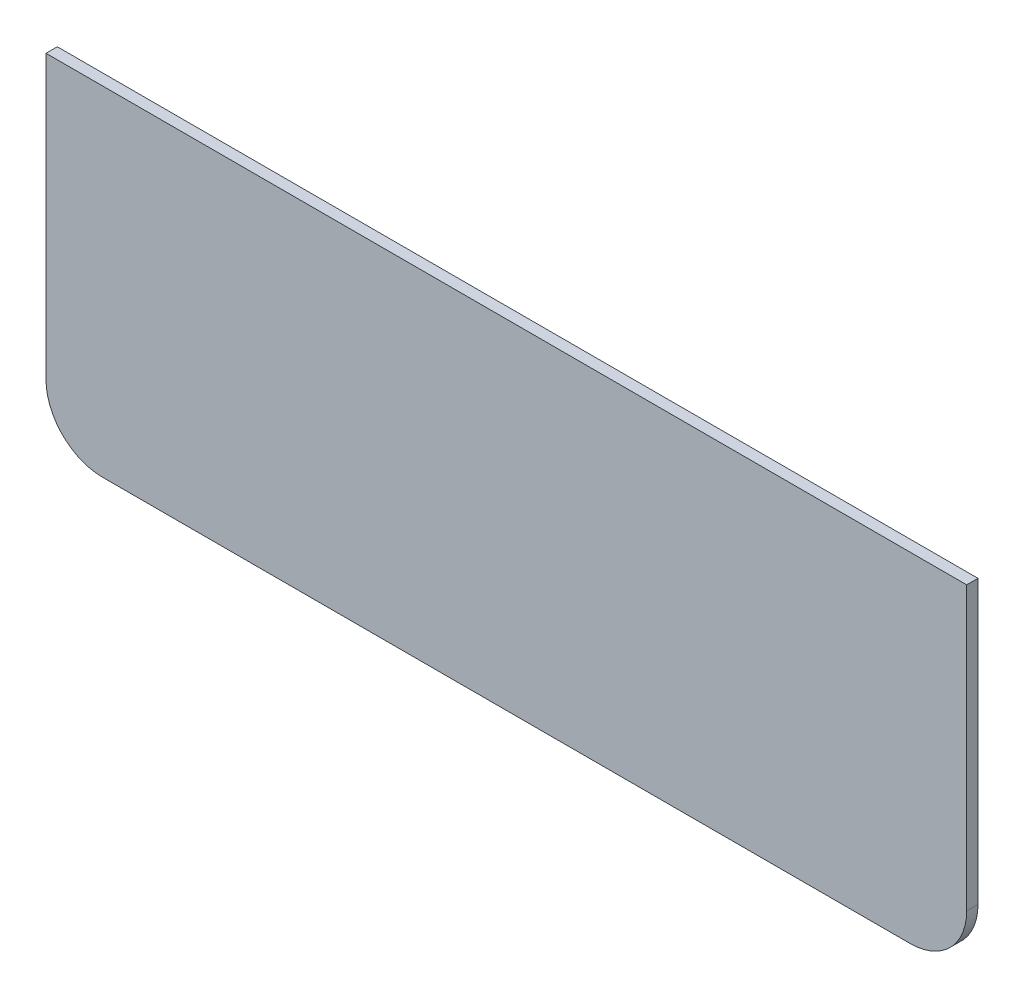
SolidWorks part; units mm, degrees
material "AISI 304"
ref_plane "Спереди" through (0, 0, 0) normal (0, 0, 1) x (1, 0, 0)
ref_plane "Сверху" through (0, 0, 0) normal (0, 1, 0) x (1, 0, 0)
ref_plane "Справа" through (0, 0, 0) normal (1, 0, 0) x (0, 0, -1)
sketch "Эскиз1" plane through (0, 0, 0) normal (0, 0, 1) x (1, 0, 0)
  line L1 (-81.5, -30) -> (81.5, -30)
  line L2 (-81.5, -30) -> (-81.5, 30)
  line L3 (-81.5, 30) -> (81.5, 30)
  line L4 (81.5, -30) -> (81.5, 30)
  line L5 (-81.5, -30) -> (81.5, 30) construction
  line L6 (-81.5, 30) -> (81.5, -30) construction
  point P0 (0, 0)
  dimension "D1" = 163
  dimension "D2" = 60
extrude "Бобышка-Вытянуть1" add sketch "Эскиз1" along normal blind 2
fillet "Скругление1" radius 10 2 edges at (81.5, -30, 1) (-81.5, -30, 1)
move or copy body "Тело-Переместить/Копировать2" [suppressed] bodies to move or copy 101 parameters "D1"=0, "D2"=0, "D3"=0
move or copy body "Тело-Переместить/Копировать1" [suppressed] bodies to move or copy 101 parameters "D1"=0, "D2"=0, "D3"=0
